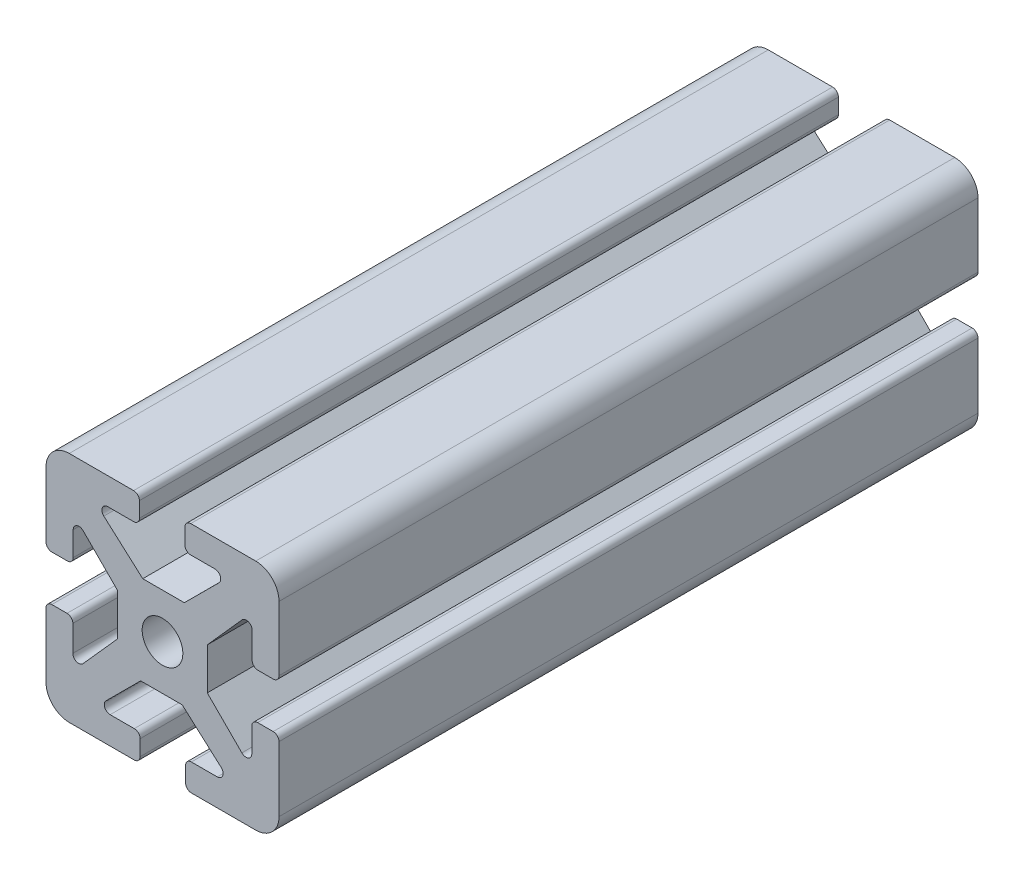
SolidWorks part; units mm, degrees
ref_plane "Front Plane" through (0, 0, 0) normal (0, 0, 1) x (1, 0, 0)
ref_plane "Top Plane" through (0, 0, 0) normal (0, 1, 0) x (1, 0, 0)
ref_plane "Right Plane" through (0, 0, 0) normal (1, 0, 0) x (0, 0, -1)
sketch "Sketch2" plane through (0, 0, 0) normal (0, 0, 1) x (1, 0, 0)
  line L0 (46.607, 139.3199) -> (233.0351, 139.3199) construction
  line L1 (0, 40) -> (40, 0) construction
  line L2 (0, 0) -> (40, 0) construction
  line L3 (0, 0) -> (0, 40) construction
  line L4 (0, 40) -> (40, 40) construction
  line L5 (40, 0) -> (40, 40) construction
  line L6 (0, 0) -> (40, 40) construction
  line L7 (19.4883, 27.6847) -> (23.7499, 27.6847)
  line L8 (23.7499, 27.6847) -> (29.6997, 33.625)
  line L9 (28.9931, 35.3327) -> (24.8456, 35.3327)
  line L10 (23.8456, 36.3327) -> (23.8456, 39)
  line L11 (24.8456, 40) -> (36, 40)
  line L12 (40, 36) -> (40, 24.9611)
  line L13 (39, 23.9611) -> (36.3883, 23.9611)
  line L14 (35.3883, 24.9611) -> (35.3883, 29.4086)
  line L15 (33.6417, 30.0739) -> (27.6847, 23.3888)
  line L16 (27.6847, 23.3888) -> (27.6847, 20.5117)
  line L17 (27.6847, 16.2501) -> (33.625, 10.3003)
  line L18 (30.0739, 6.3583) -> (23.3888, 12.3153)
  line L19 (27.6847, 20.5117) -> (27.6847, 16.2501)
  line L20 (35.3327, 11.0069) -> (35.3327, 15.1544)
  line L21 (36.3327, 16.1544) -> (39, 16.1544)
  line L22 (40, 15.1544) -> (40, 4)
  line L23 (36, 0) -> (24.9611, 0)
  line L24 (23.9611, 1) -> (23.9611, 3.6117)
  line L25 (24.9611, 4.6117) -> (29.4086, 4.6117)
  line L26 (23.3888, 12.3153) -> (20.5117, 12.3153)
  line L27 (16.2501, 12.3153) -> (10.3003, 6.375)
  line L28 (6.3583, 9.9261) -> (12.3153, 16.6112)
  line L29 (20.5117, 12.3153) -> (16.2501, 12.3153)
  line L30 (11.0069, 4.6673) -> (15.1544, 4.6673)
  line L31 (16.1544, 3.6673) -> (16.1544, 1)
  line L32 (15.1544, 0) -> (4, 0)
  line L33 (0, 4) -> (0, 15.0389)
  line L34 (1, 16.0389) -> (3.6117, 16.0389)
  line L35 (4.6117, 15.0389) -> (4.6117, 10.5914)
  line L36 (12.3153, 16.6112) -> (12.3153, 19.4883)
  line L37 (12.3153, 23.7499) -> (6.375, 29.6997)
  line L38 (9.9261, 33.6417) -> (16.6112, 27.6847)
  line L39 (12.3153, 19.4883) -> (12.3153, 23.7499)
  line L40 (4.6673, 28.9931) -> (4.6673, 24.8456)
  line L41 (3.6673, 23.8456) -> (1, 23.8456)
  line L42 (0, 24.8456) -> (0, 36)
  line L43 (4, 40) -> (15.0389, 40)
  line L44 (16.0389, 39) -> (16.0389, 36.3883)
  line L45 (15.0389, 35.3883) -> (10.5914, 35.3883)
  line L46 (16.6112, 27.6847) -> (19.4883, 27.6847)
  circle A1 centre (20, 20) radius 3.4925
  arc A2 (40, 24.9611) -> (39, 23.9611) centre (39, 24.9611) cw
  arc A3 (36.3883, 23.9611) -> (35.3883, 24.9611) centre (36.3883, 24.9611) cw
  arc A4 (24.8456, 35.3327) -> (23.8456, 36.3327) centre (24.8456, 36.3327) cw
  arc A5 (23.8456, 39) -> (24.8456, 40) centre (24.8456, 39) cw
  arc A6 (29.6997, 33.625) -> (28.9931, 35.3327) centre (28.9931, 34.3327) ccw
  arc A7 (35.3883, 29.4086) -> (33.6417, 30.0739) centre (34.3883, 29.4086) ccw
  arc A8 (40, 36) -> (36, 40) centre (36, 36) ccw
  arc A9 (35.3327, 15.1544) -> (36.3327, 16.1544) centre (36.3327, 15.1544) cw
  arc A10 (39, 16.1544) -> (40, 15.1544) centre (39, 15.1544) cw
  arc A11 (36, 0) -> (40, 4) centre (36, 4) ccw
  arc A12 (24.9611, 0) -> (23.9611, 1) centre (24.9611, 1) cw
  arc A13 (23.9611, 3.6117) -> (24.9611, 4.6117) centre (24.9611, 3.6117) cw
  arc A14 (29.4086, 4.6117) -> (30.0739, 6.3583) centre (29.4086, 5.6117) ccw
  arc A15 (33.625, 10.3003) -> (35.3327, 11.0069) centre (34.3327, 11.0069) ccw
  arc A16 (15.1544, 4.6673) -> (16.1544, 3.6673) centre (15.1544, 3.6673) cw
  arc A17 (16.1544, 1) -> (15.1544, 0) centre (15.1544, 1) cw
  arc A18 (0, 4) -> (4, 0) centre (4, 4) ccw
  arc A19 (0, 15.0389) -> (1, 16.0389) centre (1, 15.0389) cw
  arc A20 (3.6117, 16.0389) -> (4.6117, 15.0389) centre (3.6117, 15.0389) cw
  arc A21 (4.6117, 10.5914) -> (6.3583, 9.9261) centre (5.6117, 10.5914) ccw
  arc A22 (10.3003, 6.375) -> (11.0069, 4.6673) centre (11.0069, 5.6673) ccw
  arc A23 (4.6673, 24.8456) -> (3.6673, 23.8456) centre (3.6673, 24.8456) cw
  arc A24 (1, 23.8456) -> (0, 24.8456) centre (1, 24.8456) cw
  arc A25 (4, 40) -> (0, 36) centre (4, 36) ccw
  arc A26 (15.0389, 40) -> (16.0389, 39) centre (15.0389, 39) cw
  arc A27 (16.0389, 36.3883) -> (15.0389, 35.3883) centre (15.0389, 36.3883) cw
  arc A28 (10.5914, 35.3883) -> (9.9261, 33.6417) centre (10.5914, 34.3883) ccw
  arc A29 (6.375, 29.6997) -> (4.6673, 28.9931) centre (5.6673, 28.9931) ccw
  point P24 (40, 23.9611)
  point P31 (23.8456, 40)
  dimension "D1" = 40
  dimension "D3" = 1
  dimension "D4" = 4
  dimension "D2" = 40
  dimension "D5" = 4
extrude "Boss-Extrude1" add sketch "Sketch2" along normal blind 120
